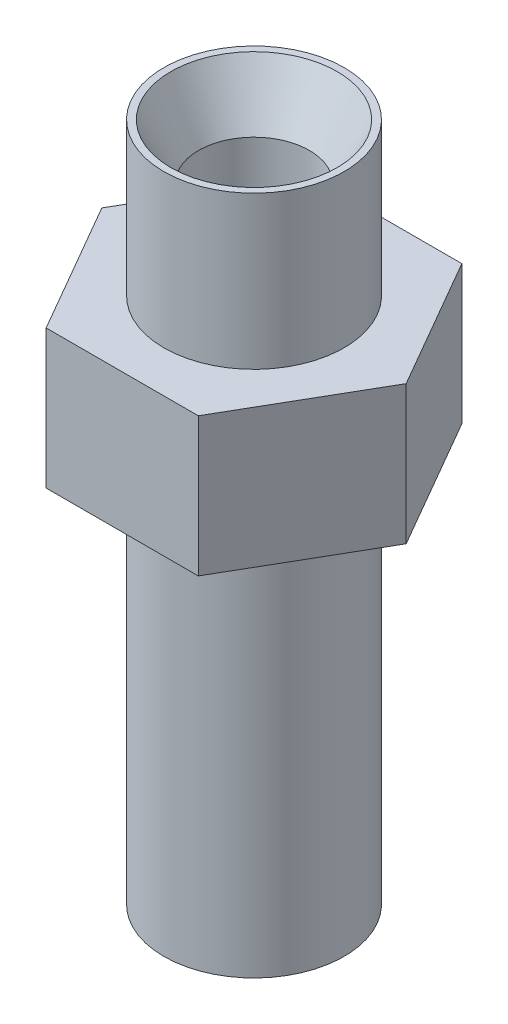
SolidWorks part; units mm, degrees
ref_plane "Front Plane" through (0, 0, 0) normal (0, 0, 1) x (1, 0, 0)
ref_plane "Top Plane" through (0, 0, 0) normal (0, 1, 0) x (1, 0, 0)
ref_plane "Right Plane" through (0, 0, 0) normal (1, 0, 0) x (0, 0, -1)
sketch "Sketch1" plane through (0, 0, 0) normal (0, 1, 0) x (1, 0, 0)
  line L1 (10.9697, 0) -> (5.4848, 9.5)
  line L2 (5.4848, 9.5) -> (-5.4848, 9.5)
  line L3 (-5.4848, 9.5) -> (-10.9697, 0)
  line L4 (-10.9697, 0) -> (-5.4848, -9.5)
  line L5 (-5.4848, -9.5) -> (5.4848, -9.5)
  line L6 (5.4848, -9.5) -> (10.9697, 0)
  circle A0 centre (0, 0) radius 9.5 construction
  dimension "D1" = 19
extrude "Boss-Extrude1" add sketch "Sketch1" along normal blind 10
sketch "Sketch2" plane through (0, 10, 0) normal (0, 1, 0) x (1, 0, 0)
  circle A0 centre (0, 0) radius 6.5
  dimension "D1" = 13
extrude "Boss-Extrude2" add sketch "Sketch2" along normal blind 11 and the other way blind 38
sketch "Sketch3" plane through (0, 21, 0) normal (0, 1, 0) x (1, 0, 0)
  circle A0 centre (0, 0) radius 4
  dimension "D1" = 8
extrude "Cut-Extrude1" cut sketch "Sketch3" against normal blind 57
chamfer "Chamfer1" distance 2 angle 63 1 edges at (0, 21, 4)
chamfer "Chamfer2" distance 2 angle 38 1 edges at (0, -28, 4)
